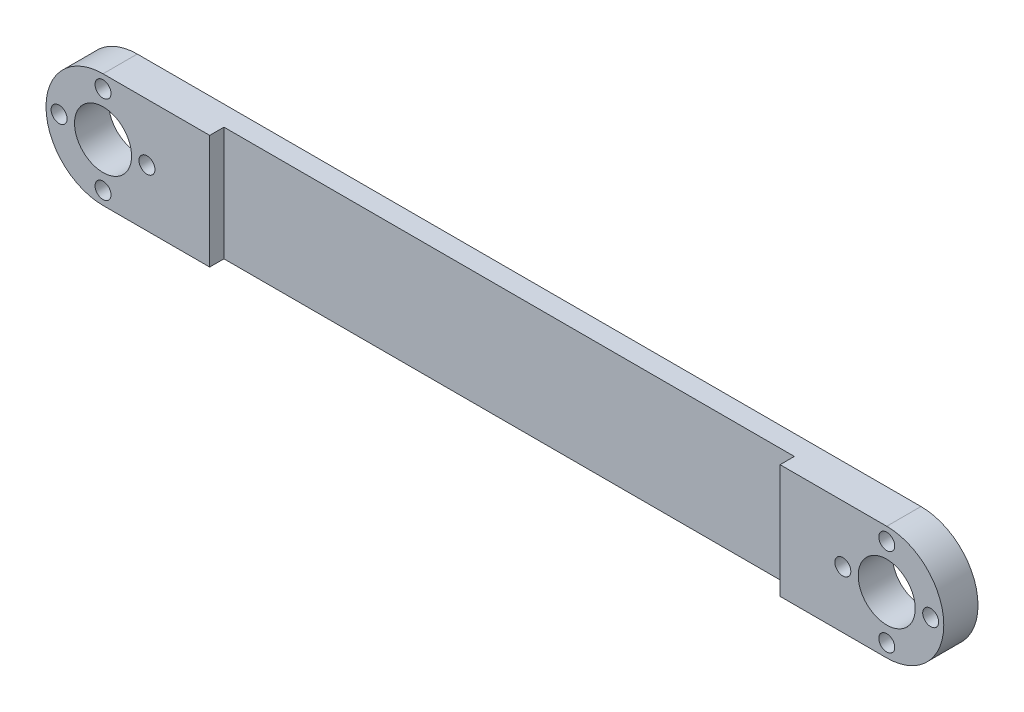
SolidWorks part; units mm, degrees
material "ABS"
ref_plane "Front Plane" through (0, 0, 0) normal (0, 0, 1) x (1, 0, 0)
ref_plane "Top Plane" through (0, 0, 0) normal (0, 1, 0) x (1, 0, 0)
ref_plane "Right Plane" through (0, 0, 0) normal (1, 0, 0) x (0, 0, -1)
sketch "Sketch1" plane through (0, 0, 0) normal (0, 0, 1) x (1, 0, 0)
  line L1 (0, 0) -> (-199.898, 0)
  line L2 (0, 0) -> (0, -25.4)
  line L3 (0, -25.4) -> (-199.898, -25.4)
  line L4 (-199.898, 0) -> (-199.898, -25.4)
  circle A0 centre (-187.198, -12.7) radius 12.7
  circle A1 centre (-12.7, -12.7) radius 12.7
  dimension "D3" = 25.4
  dimension "D5" = 25.4
  dimension "D1" = 199.898
  dimension "D2" = 25.4
  dimension "D4" = 12.7
  dimension "D6" = 12.7
  dimension "D7" = 12.7
  dimension "D8" = 12.7
extrude "Boss-Extrude1" add sketch "Sketch1" along normal blind 7.62 contours A1 L1 A0 L3 | A0 | A1
sketch "Sketch2" plane through (0, 0, 7.62) normal (0, 0, 1) x (1, 0, 0)
  line L0 (-12.7, 0) -> (-187.198, 0) construction
  circle A0 centre (-12.7, -12.7) radius 6.35
  arc A1 (-12.7, -25.4) -> (-12.7, 0) centre (-12.7, -12.7) ccw construction
  point P7 (0, -12.7)
  dimension "D1" = 12.7
  dimension "D2" = 12.7
  dimension "D3" = 12.7
extrude "Cut-Extrude1" cut sketch "Sketch2" against normal blind 7.62
sketch "Sketch3" plane through (0, 0, 7.62) normal (0, 0, 1) x (1, 0, 0)
  line L0 (-12.7, 0) -> (-187.198, 0) construction
  circle A0 centre (-2.921, -12.7) radius 1.778
  circle A1 centre (-12.7, -12.7) radius 6.35 construction
  dimension "D1" = 3.556
  dimension "D2" = 12.7
  dimension "D3" = 9.779
extrude "Cut-Extrude2" cut sketch "Sketch3" against normal blind 7.62
pattern_circular "CirPattern1" count 4 over 360 about axis through (-12.7, -12.7, 0) along (0, 0, 1) of "Cut-Extrude2"
ref_plane "Plane1" through (-99.949, 0, 0) normal (1, 0, 0) x (0, 0, -1)
mirror "Mirror1" about plane through (-99.949, 0, 0) normal (1, 0, 0) of "Cut-Extrude1", "CirPattern1", "Cut-Extrude2"
sketch "Sketch4" plane through (0, -25.4, 0) normal (0, -1, 0) x (1, 0, 0)
  line L0 (-12.7, 7.62) -> (-187.198, 7.62) construction
  line L1 (-163.449, 7.62) -> (-36.449, 7.62)
  line L2 (-163.449, 7.62) -> (-163.449, 4.445)
  line L3 (-163.449, 4.445) -> (-36.449, 4.445)
  line L4 (-36.449, 7.62) -> (-36.449, 4.445)
  line L5 (-99.949, -4.191) -> (-99.949, 4.191) construction
  dimension "D1" = 127
  dimension "D2" = 63.5
  dimension "D3" = 3.175
extrude "Cut-Extrude3" cut sketch "Sketch4" against normal blind 25.4
